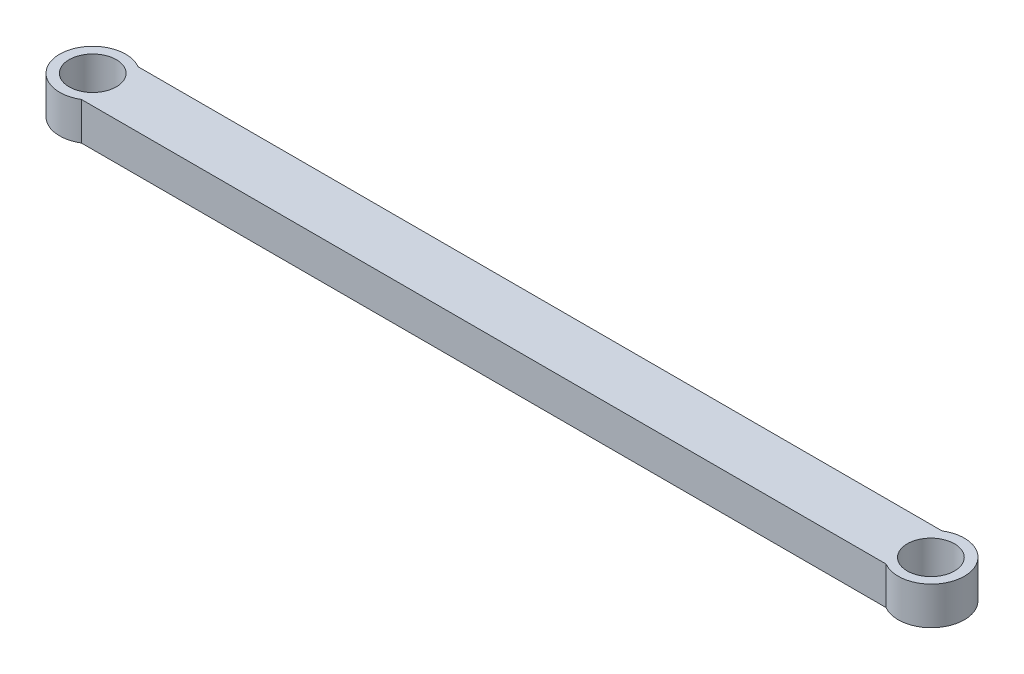
SolidWorks part; units mm, degrees
ref_plane "Front Plane" through (0, 0, 0) normal (0, 0, 1) x (1, 0, 0)
ref_plane "Top Plane" through (0, 0, 0) normal (0, 1, 0) x (1, 0, 0)
ref_plane "Right Plane" through (0, 0, 0) normal (1, 0, 0) x (0, 0, -1)
sketch "Sketch2" plane through (0, 0, 0) normal (0, 1, 0) x (1, 0, 0)
  line L0 (0, 1.75) -> (0, 1.25)
  line L1 (0, -1.25) -> (0, -1.75)
  line L2 (0, 1.5) -> (44.3835, 1.5)
  line L3 (0, -1.5) -> (44.3835, -1.5)
  line L4 (44.3835, 1.7605) -> (44.3835, 1.2395)
  line L5 (44.3835, -1.2605) -> (44.3835, -1.7395)
  circle A0 centre (0, 0) radius 1.75
  circle A1 centre (0, 0) radius 1.25
  circle A2 centre (44.3835, 0.0105) radius 1.75
  circle A3 centre (44.3835, -0.0105) radius 1.25
  point P22 (44.3835, 1.5)
  dimension "D1" = 3.5
  dimension "D3" = 3.5
  dimension "D2" = 0.5
extrude "Boss-Extrude1" add sketch "Sketch2" along normal blind 2 contours A2 L2 A0 L3 | A1 L1 L3 A0 L2 L0 | A1 L0 A0 L1 | A3 L5 A2 L4 | A3 L4 L2 A2 L3 L5 | L2 A0 L0 | L1 A0 L3 | L4 A2 L2 | L3 A2 L5
sketch "Sketch3" plane through (0, 0, 0) normal (0, -1, 0) x (1, 0, 0)
  circle A0 centre (0, 0) radius 1.25
  circle A1 centre (44.3835, 0.0105) radius 1.25
  dimension "D1" = 2.5
  dimension "D2" = 2.5
